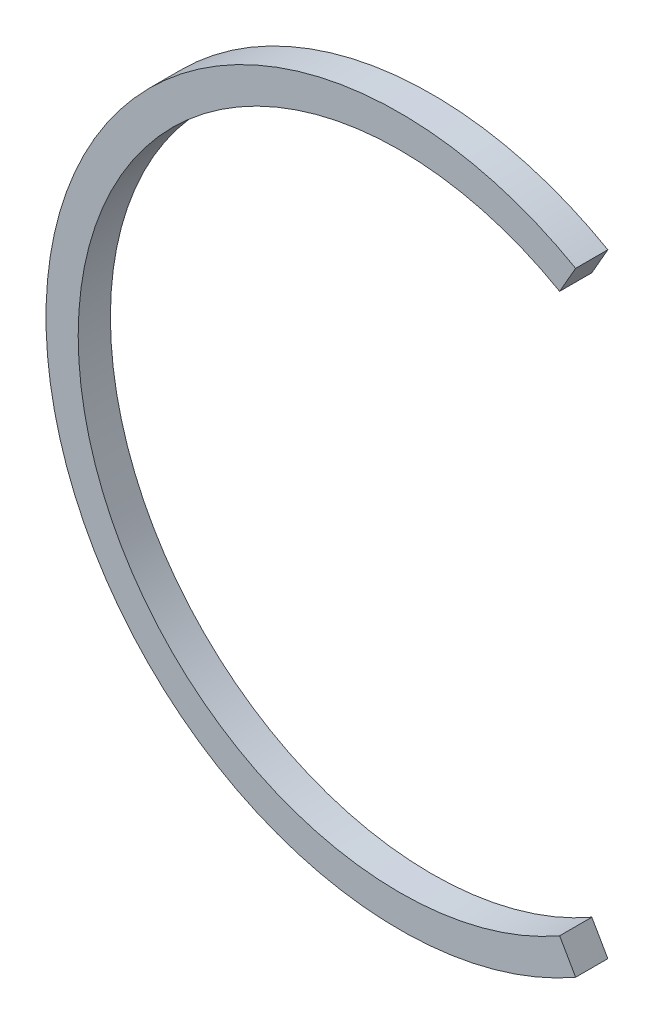
SolidWorks part; units mm, degrees
ref_plane "Front" through (0, 0, 0) normal (0, 0, 1) x (1, 0, 0)
ref_plane "Top" through (0, 0, 0) normal (0, 1, 0) x (1, 0, 0)
ref_plane "Right" through (0, 0, 0) normal (1, 0, 0) x (0, 0, -1)
sketch "Sketch1" plane through (0, 0, 0) normal (0, 0, 1) x (1, 0, 0)
  line L0 (0, 9.2456) -> (7.206, 9.2456) construction
  line L1 (0, -9.2456) -> (7.206, -9.2456) construction
  line L2 (0, 9.2456) -> (0, -9.2456) construction
  line L3 (-11.7221, 0) -> (-10.6553, 0) construction
  line L4 (0, 0) -> (5.2966, 9.2456) construction
  line L5 (0, 0) -> (5.2966, -9.2456) construction
  line L6 (2.7578, -10.2922) -> (0, 0) construction
  circle A0 centre (0, 0) radius 11.7221 construction
  circle A1 centre (0, 0) radius 11.1125
  circle A2 centre (0, 0) radius 10.6553 construction
  point P15 (2.7578, -10.2922)
  dimension "D1" = 15
  dimension "Ring OD" = 23.4442
  dimension "For OD" = 22.225
  dimension "Gap" = 18.4912
  dimension "Ring Width" = 1.0668
sketch "Sketch3" plane through (0, 0, 0) normal (0, 1, 0) x (1, 0, 0)
  line L0 (0, -0.5334) -> (0, 0.5334)
  point P4 (0, 0)
  dimension "Ring Thickness" = 1.0668
sketch "Sketch2" plane through (0, 0, 0) normal (0, 0, 1) x (1, 0, 0)
  line L0 (0, 0) -> (5.2966, -9.2456) construction
  line L1 (0, 0) -> (5.2966, 9.2456) construction
  line L2 (5.2966, -9.2456) -> (5.8269, -10.1713)
  line L3 (5.2966, 9.2456) -> (5.8269, 10.1713)
  circle A0 centre (0, 0) radius 11.7221 construction
  circle A1 centre (0, 0) radius 10.6553 construction
  arc A2 (5.8269, 10.1713) -> (5.8269, -10.1713) centre (0, 0) ccw
  arc A3 (5.2966, 9.2456) -> (5.2966, -9.2456) centre (0, 0) ccw
extrude "Boss-Extrude1" add sketch "Sketch2" against normal up to vertex (0.5334 mm away) and the other way up to vertex (0.5334 mm away) up to point (0, 0, -0.5334) other way up to point (0, 0, 0.5334)
